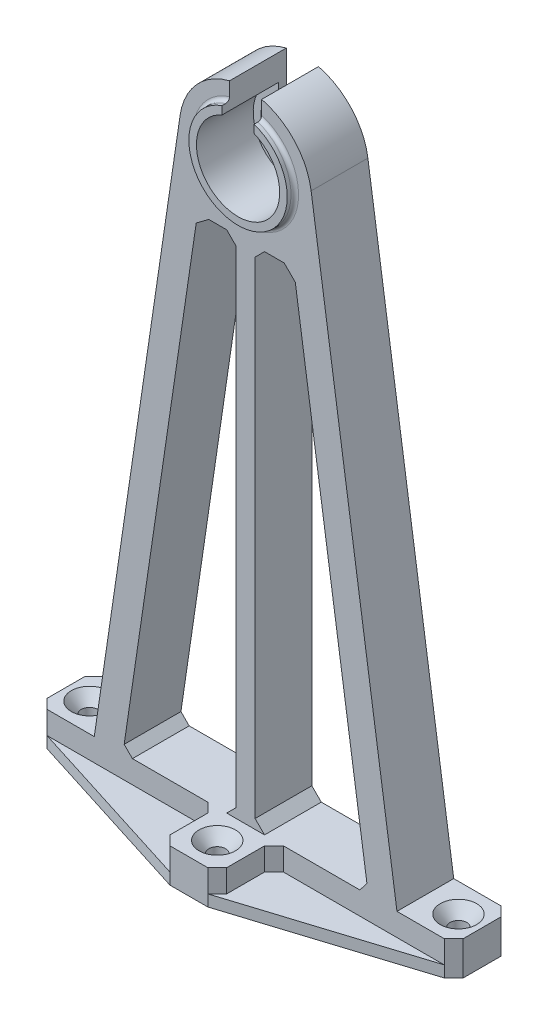
SolidWorks part; units mm, degrees
ref_plane "Front Plane" through (0, 0, 0) normal (0, 0, 1) x (1, 0, 0)
ref_plane "Top Plane" through (0, 0, 0) normal (0, 1, 0) x (1, 0, 0)
ref_plane "Right Plane" through (0, 0, 0) normal (1, 0, 0) x (0, 0, -1)
sketch "Sketch1" plane through (0, 0, 0) normal (0, 0, 1) x (1, 0, 0)
  line L0 (17.5, 0) -> (-17.5, 0)
  line L3 (-55, -160) -> (55, -160)
  line L4 (-32.4186, -151) -> (-12.6942, -17.5)
  line L5 (-55, -160) -> (55, -160)
  line L7 (-32.4186, -151) -> (32.4186, -151)
  line L9 (-12.6942, -17.5) -> (12.6942, -17.5)
  line L10 (12.6942, -17.5) -> (32.4186, -151)
  line L11 (-40, -151) -> (-17.3121, 2.5578)
  line L15 (-55, -160) -> (-55, -151)
  line L19 (55, -160) -> (55, -151)
  line L20 (40, -151) -> (17.3121, 2.5578)
  line L21 (-55, -151) -> (-40, -151)
  line L22 (40, -151) -> (55, -151)
  line L23 (0, -17.5) -> (0, -151) construction
  line L24 (-4.25, 7.5) -> (4.25, 7.5)
  line L25 (-2.5, -17.5) -> (2.5, -17.5)
  line L26 (-2.5, -17.5) -> (-2.5, -151)
  line L27 (-2.5, -151) -> (2.5, -151)
  line L28 (2.5, -17.5) -> (2.5, -151)
  line L29 (-2.5, -17.5) -> (2.5, -151) construction
  line L30 (-2.5, -151) -> (2.5, -17.5) construction
  line L31 (-4.25, 7.5) -> (-4.25, 17.5)
  line L32 (-4.25, 17.5) -> (4.25, 17.5)
  line L33 (4.25, 17.5) -> (4.25, 7.5)
  circle A0 centre (0, 0) radius 17.5
  circle A1 centre (0, 0) radius 11
  point P4 (0, 0)
  point P9 (0, -160)
  point P10 (0, -84.25)
  point P17 (0, -17.5)
  point P31 (0, 11)
  point P38 (0, 7.5)
  dimension "D2" = 22
  dimension "D1" = 160
  dimension "D3" = 35
  dimension "D4" = 110
  dimension "D5" = 9
  dimension "D6" = 7.5
  dimension "D7" = 15
  dimension "D8" = 7.5
  dimension "D9" = 5
  dimension "D10" = 8.5
  dimension "D11" = 10
extrude "Boss-Extrude1" add sketch "Sketch1" along normal blind 15 contours A0 L25 L9 L10 L7 L4 L11 L21 L15 L3 L19 L22 L20 | L28 L25 L9 L26 L7 | A1 L0 A0 | A1 L31 A0 L0 | A1 L0 A0 L33
sketch "Sketch4" plane through (0, -160, 0) normal (0, -1, 0) x (1, 0, 0)
  line L1 (-7.5, 30) -> (7.5, 30)
  line L2 (-7.5, 30) -> (-7.5, 15)
  line L3 (-7.5, 15) -> (7.5, 15)
  line L4 (7.5, 30) -> (7.5, 15)
  line L5 (-55, 15) -> (55, 15) construction
  point P7 (0, 15)
  dimension "D1" = 15
  dimension "D2" = 15
extrude "Boss-Extrude2" add sketch "Sketch4" against normal up to surface (9 mm away) up to face at (-17.4593, -151, 7.5)
sketch "Sketch2" plane through (0, -151, 0) normal (0, 1, 0) x (1, 0, 0)
  line L0 (-7.5, -22.5) -> (7.5, -22.5) construction
  line L1 (-7.5, -30) -> (-7.5, -15) construction
  line L2 (0, 0) -> (0, -15) construction
  line L3 (7.5, -15) -> (7.5, -30) construction
  line L5 (-2.5, -15) -> (2.5, -15) construction
  circle A0 centre (-48.75, -7.5) radius 2.2
  circle A1 centre (48.75, -7.5) radius 2.2
  circle A2 centre (0, -22.5) radius 2.2
  point P0 (0, -7.5)
  dimension "D3" = 4.4
  dimension "D1" = 48.75
extrude "Cut-Extrude1" cut sketch "Sketch2" against normal through all both and the other way through all
ref_plane "Plane1" through (-48.75, 0, 0) normal (1, 0, 0) x (0, 0, -1)
sketch "Sketch3" plane through (-48.75, 0, 0) normal (1, 0, 0) x (0, 0, -1)
  line L0 (-7.5, -151) -> (-7.5, -154)
  line L1 (-15, -151) -> (0, -151) construction
  line L2 (-7.5, -154) -> (-5.3, -154)
  line L3 (-5.3, -154) -> (-2.6921, -151)
  line L4 (-2.6921, -151) -> (-7.5, -151)
  line L6 (-7.5, -151) -> (-2.6921, -151)
  line L7 (-7.5, -151) -> (-7.5, 33.0085)
  line L8 (-7.5, 33.0085) -> (-2.6921, 33.0085)
  line L9 (-2.6921, -151) -> (-2.6921, 33.0085)
  dimension "D1" = 3
  dimension "D2" = 131
  dimension "D3" = 2.2
revolve "Cut-Revolve2" cut sketch "Sketch3" angle 360 about L0
sketch "Sketch5" plane through (0, 0, 0) normal (1, 0, 0) x (0, 0, -1)
  line L0 (-22.5, -151) -> (-22.5, -154)
  line L1 (-15, -151) -> (-30, -151) construction
  line L2 (-22.5, -154) -> (-20.3, -154)
  line L3 (-20.3, -154) -> (-17.6921, -151)
  line L4 (-17.6921, -151) -> (-22.5, -151)
  dimension "D1" = 2.2
  dimension "D2" = 131
  dimension "D3" = 3
revolve "Cut-Revolve3" cut sketch "Sketch5" angle 360 about L0
mirror "Mirror1" about plane through (0, 0, 0) normal (1, 0, 0) of "Cut-Revolve2"
chamfer "Chamfer1" distance 2.5 angle 45 8 edges at (-12.6942, -17.5, 7.5) (12.6942, -17.5, 7.5) (32.4186, -151, 7.5) (-32.4186, -151, 7.5) (2.5, -17.5, 7.5) (-2.5, -17.5, 7.5) (2.5, -151, 7.5) (-2.5, -151, 7.5)
chamfer "Chamfer2" distance 2.5 angle 45 8 edges at (-7.5, -155.5, 30) (-7.5, -155.5, 15) (7.5, -155.5, 30) (7.5, -155.5, 15) (55, -155.5, 0) (55, -155.5, 15) (-55, -155.5, 0) (-55, -155.5, 15)
sketch "Sketch7" plane through (0, -160, 0) normal (0, -1, 0) x (1, 0, 0)
  line L0 (-52.5, 15) -> (-5, 30)
  line L1 (-5, 30) -> (5, 30)
  line L2 (5, 30) -> (52.5, 15)
  point P8 (0, 0)
  point P9 (-7.991, 30)
  point P10 (0, 0)
  point P11 (-52.5, 15)
  point P13 (0, 0)
  point P14 (52.5, 15)
  point P16 (0, 0)
  point P17 (5, 30)
  point P19 (-5, 30)
extrude "Boss-Extrude5" add sketch "Sketch7" against normal blind 3
sketch "Sketch6" plane through (0, 0, 0) normal (0, 0, -1) x (-1, 0, 0)
  line L0 (-4.25, 10.1458) -> (-4.25, 7.9333)
  line L5 (4.25, 10.1458) -> (4.25, 7.9333)
  line L6 (4.25, 10.1458) -> (4.25, 16.9761) construction
  line L7 (-4.25, 16.9761) -> (-4.25, 10.1458) construction
  circle A0 centre (0, 0) radius 11
  arc A1 (-4.25, 10.1458) -> (4.25, 10.1458) centre (0, 0) ccw construction
  circle A2 centre (0, 0) radius 9
  arc M18 (4.25, 10.1458) -> (-4.25, 10.1458) centre (0, 0) cw
  dimension "D1" = 2
extrude "Boss-Extrude3" add sketch "Sketch6" against normal blind 2 contours A0 A2 M18
sketch "Sketch9" plane through (0, 0, 15) normal (0, 0, 1) x (1, 0, 0)
  circle A0 centre (0, 0) radius 13
  arc A1 (-4.25, 10.1458) -> (4.25, 10.1458) centre (0, 0) ccw construction
  line M7 (4.25, 16.9761) -> (4.25, 10.1458)
  arc M8 (4.25, 10.1458) -> (-4.25, 10.1458) centre (0, 0) cw
  line M9 (-4.25, 10.1458) -> (-4.25, 16.9761)
  dimension "D1" = 2
extrude "Boss-Extrude6" add sketch "Sketch9" along normal blind 2 contours A0 M9 M7 M8
fillet "Fillet2" radius 1 1 edges at (0, -13, 15)
